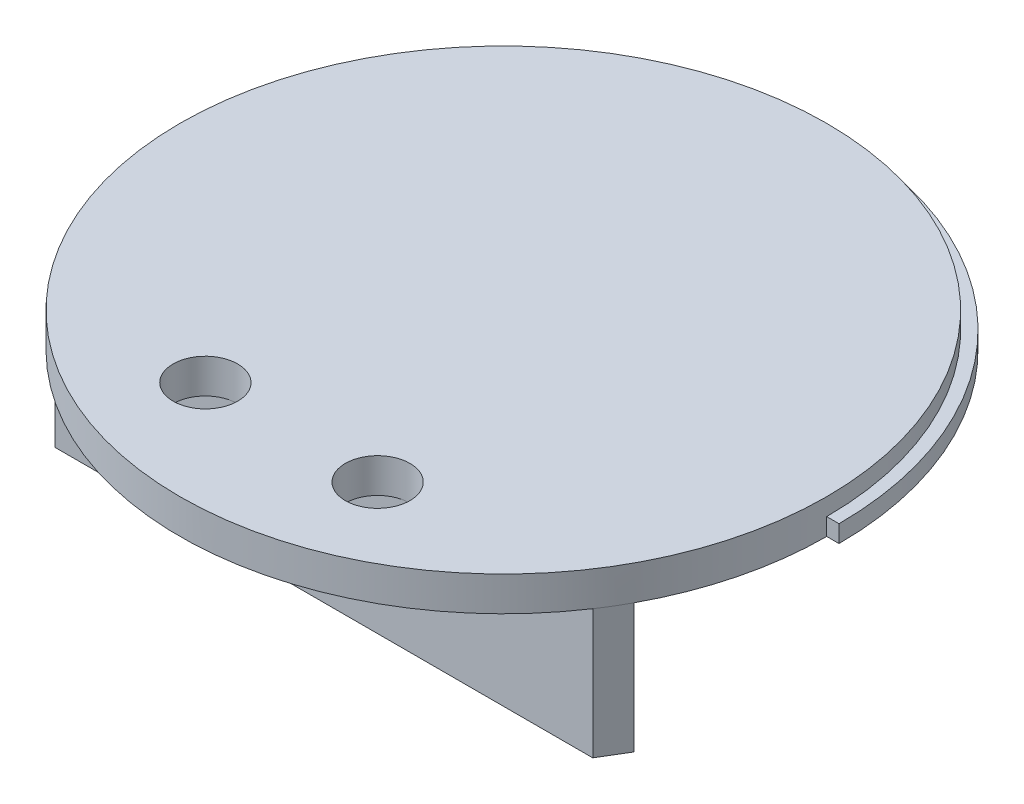
SolidWorks part; units mm, degrees
ref_plane "Front Plane" through (0, 0, 0) normal (0, 0, 1) x (1, 0, 0)
ref_plane "Top Plane" through (0, 0, 0) normal (0, 1, 0) x (1, 0, 0)
ref_plane "Right Plane" through (0, 0, 0) normal (1, 0, 0) x (0, 0, -1)
sketch "Sketch1" plane through (0, 0, 0) normal (0, 1, 0) x (1, 0, 0)
  line L0 (-49.5046, 0) -> (-47.6885, 0)
  line L1 (49.5046, 0) -> (47.6885, 0)
  arc A0 (-47.6885, 0) -> (47.6885, 0) centre (0, 0) ccw
  arc A1 (49.5046, 0) -> (-49.5046, 0) centre (0, 0) ccw
  dimension "D1" = 95.377
  dimension "D2" = 99.0092
extrude "Boss-Extrude1" add sketch "Sketch1" along normal blind 2.54
sketch "Sketch2" plane through (0, 2.54, 0) normal (0, 1, 0) x (1, 0, 0)
  circle A0 centre (0, 0) radius 47.6885
extrude "Boss-Extrude2" add sketch "Sketch2" along normal blind 2.54
sketch "Sketch3" plane through (0, 0, 0) normal (0, -1, 0) x (1, 0, 0)
  circle A0 centre (12.7, 31.2354) radius 4.7625
  circle A1 centre (-12.7, 31.2354) radius 4.7625
  circle A2 centre (-12.7, 31.2354) radius 12.7 construction
  circle A3 centre (-12.7, 31.2354) radius 13.97 construction
  circle A4 centre (12.7, 31.2354) radius 12.7 construction
  circle A5 centre (12.7, 31.2354) radius 13.97 construction
  arc A6 (47.6885, 0) -> (-47.6885, 0) centre (0, 0) ccw construction
  point P11 (0, 0)
  dimension "D1" = 9.525
  dimension "D2" = 25.4
  dimension "D3" = 27.94
extrude "Cut-Extrude1" cut sketch "Sketch3" against normal blind 5.08
sketch "Sketch4" plane through (0, 0, 0) normal (0, -1, 0) x (1, 0, 0)
  line L0 (41.9594, 22.6629) -> (-41.9594, 22.6629)
  line L1 (39.6659, 26.4729) -> (-39.6659, 26.4729)
  line L2 (39.6659, 26.4729) -> (41.9594, 22.6629)
  line L4 (-39.6659, 26.4729) -> (-41.9594, 22.6629)
  arc A0 (47.6885, 0) -> (-47.6885, 0) centre (0, 0) ccw construction
  circle A1 centre (12.7, 31.2354) radius 4.7625 construction
  point P7 (0, 0)
  point P9 (0, 0)
  point P10 (0, 0)
  point P11 (42.6576, 21.3195)
  dimension "D1" = 3.81
extrude "Boss-Extrude4" add sketch "Sketch4" along normal blind 19.05
sketch "Sketch6" plane through (0, 0, 0) normal (0, -1, 0) x (1, 0, 0)
  line L0 (41.9594, -26.2701) -> (-41.9594, -26.2701)
  arc A0 (-49.5046, 0) -> (49.5046, 0) centre (0, 0) ccw construction
  point P5 (0, 0)
